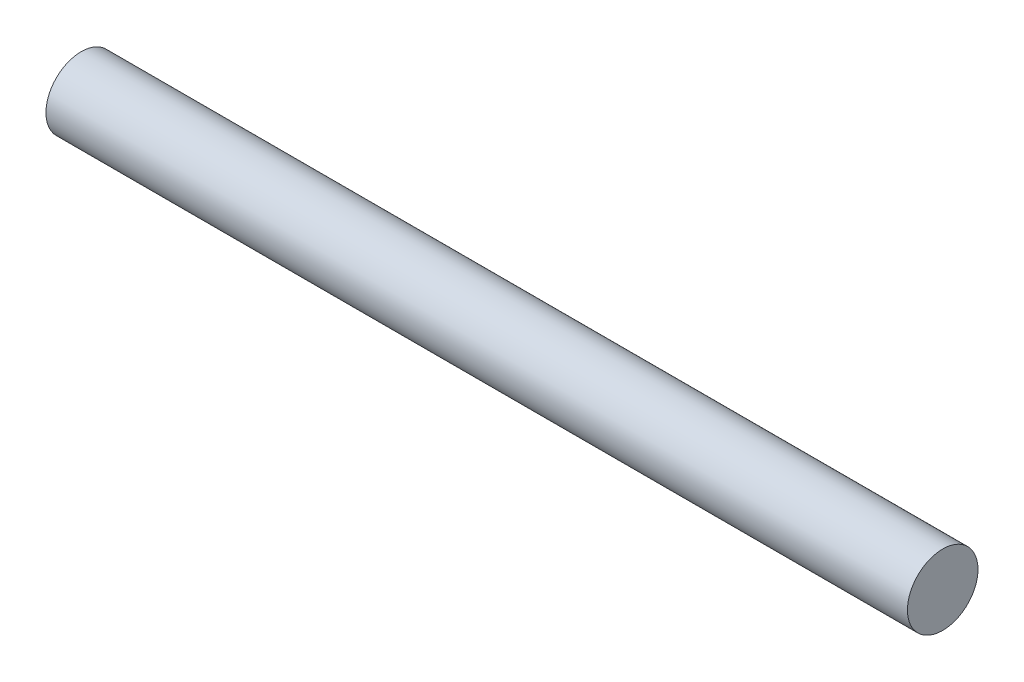
SolidWorks part; units mm, degrees
ref_plane "Front Plane" through (0, 0, 0) normal (0, 0, 1) x (1, 0, 0)
ref_plane "Top Plane" through (0, 0, 0) normal (0, 1, 0) x (1, 0, 0)
ref_plane "Right Plane" through (0, 0, 0) normal (1, 0, 0) x (0, 0, -1)
sketch "Sketch1" plane through (0, 0, 0) normal (1, 0, 0) x (0, 0, -1)
  circle A0 centre (0, 0) radius 10.668
  dimension "D1" = 21.336
extrude "Boss-Extrude1" add sketch "Sketch1" along normal blind 260.35
